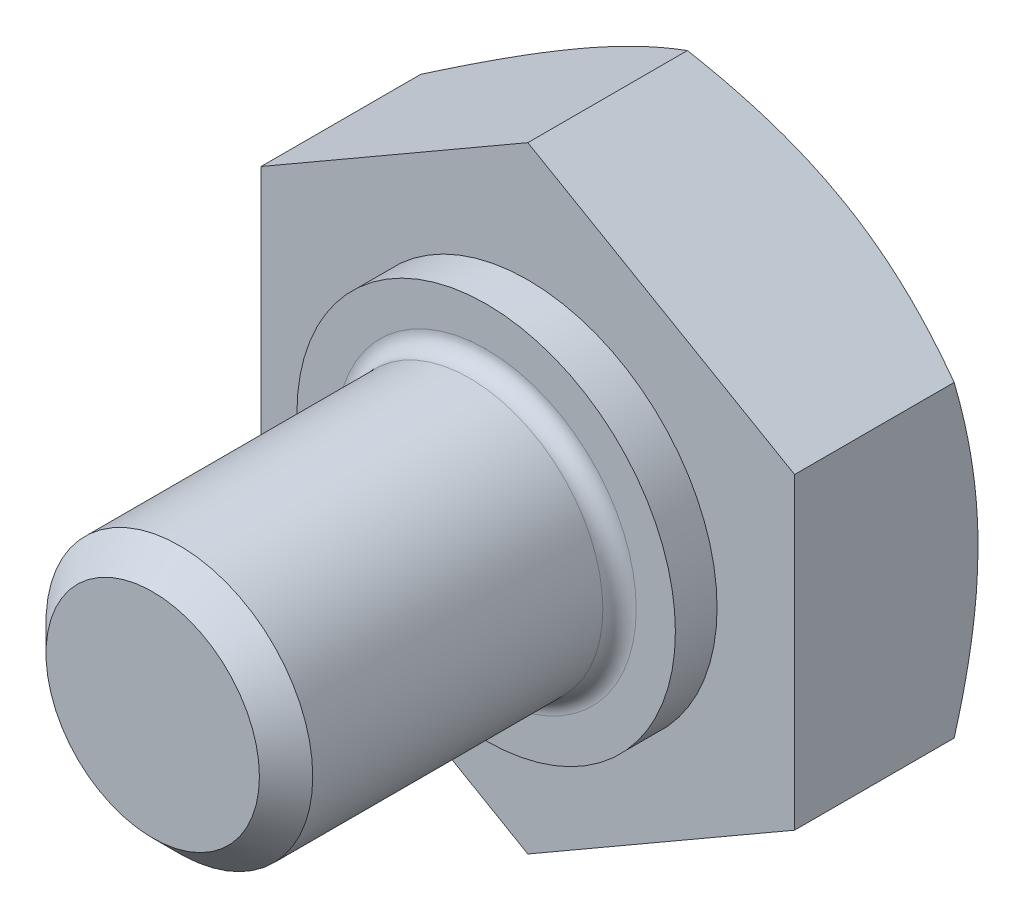
SolidWorks part; units mm, degrees
ref_plane "Přední rovina" through (0, 0, 0) normal (0, 0, 1) x (1, 0, 0)
ref_plane "Vrchní rovina" through (0, 0, 0) normal (0, 1, 0) x (1, 0, 0)
ref_plane "Pravá rovina" through (0, 0, 0) normal (1, 0, 0) x (0, 0, -1)
sketch "Skica1" plane through (0, 0, 0) normal (0, 0, 1) x (1, 0, 0)
  line L1 (1.6, -0.9238) -> (1.6, 0.9238)
  line L2 (1.6, 0.9238) -> (0, 1.8475)
  line L3 (0, 1.8475) -> (-1.6, 0.9238)
  line L4 (-1.6, 0.9238) -> (-1.6, -0.9238)
  line L5 (-1.6, -0.9238) -> (0, -1.8475)
  line L6 (0, -1.8475) -> (1.6, -0.9238)
  circle A0 centre (0, 0) radius 1.6 construction
  dimension "s" = 3.2
extrude "Vysunout1" add sketch "Skica1" along normal blind 1.1
sketch "Skica2" plane through (0, 0, 0) normal (0, 1, 0) x (1, 0, 0)
  line L0 (1.6, 0) -> (3.5053, 0)
  line L1 (3.5053, 0) -> (3.5053, -1.1)
  line L2 (3.5053, -1.1) -> (1.6, 0)
  line L3 (1.6, -1.1) -> (0, -1.1) construction
  line L4 (0, 0) -> (0, -1.1) construction
  dimension "D1" = 30
revolve "Odebrat otočením1" cut sketch "Skica2" angle 360 about L4
sketch "Skica3" plane through (0, 0, 1.1) normal (0, 0, 1) x (1, 0, 0)
  circle A0 centre (0, 0) radius 1.135
  dimension "dw" = 2.27
extrude "Vysunout2" add sketch "Skica3" along normal blind 0.25
sketch "Skica4" plane through (0, 0, 1.35) normal (0, 0, 1) x (1, 0, 0)
  circle A0 centre (0, 0) radius 0.8
  dimension "M" = 1.6
extrude "Vysunout3" add sketch "Skica4" along normal blind 2
cosmetic thread "Kosmetický závit1" parameters "D2"=1.2
chamfer "Zkosit1" distance 0.16 angle 45 1 edges at (0.8, 0, 3.35)
fillet "Zaoblit1" radius 0.1 1 edges at (0.8, 0, 1.35)
equation "\"D1@Zkosit1\" = \"M@Skica4\" * 0.1"
